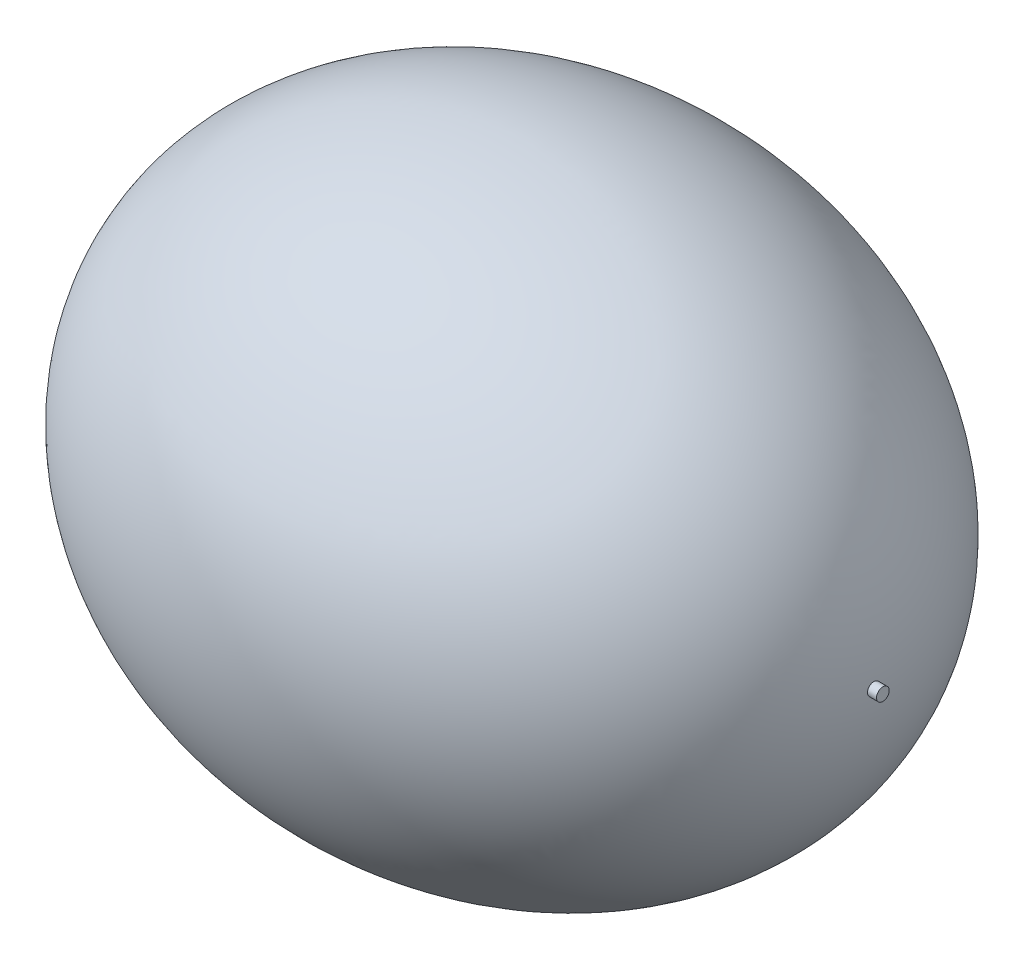
SolidWorks part; units mm, degrees
ref_plane "Front Plane" through (0, 0, 0) normal (0, 0, 1) x (1, 0, 0)
ref_plane "Top Plane" through (0, 0, 0) normal (0, 1, 0) x (1, 0, 0)
ref_plane "Right Plane" through (0, 0, 0) normal (1, 0, 0) x (0, 0, -1)
sketch "Sketch1" plane through (0, 0, 0) normal (0, 1, 0) x (1, 0, 0)
  line L0 (0, 0) -> (400, 0)
  line L1 (0, 0) -> (-400, 0)
  line L2 (0, 0) -> (0, 325)
  line L3 (399.4169, 0) -> (399.4169, 4)
  line L4 (399.4169, 4) -> (409.4169, 4)
  line L5 (409.4169, 4) -> (409.4169, 0)
  line L6 (409.4169, 0) -> (399.4169, 0)
  ellipse E0 centre (0, 0) end of major axis (-400, 0) minor radius 325
revolve "Revolve3" add sketch "Sketch1" angle 360 about L1
sketch "Sketch4" plane through (0, 0, 0) normal (0, 0, 1) x (1, 0, 0)
  line L0 (399.9697, 0) -> (409.9697, 0)
  line L1 (399.9697, 4) -> (399.9697, -4) construction
  line L2 (409.9697, 0) -> (409.9697, 7)
  line L3 (409.9697, 7) -> (399.9697, 7)
  line L4 (399.9697, 7) -> (399.9697, 0)
revolve "Revolve4" add sketch "Sketch4" angle 360 about L0
